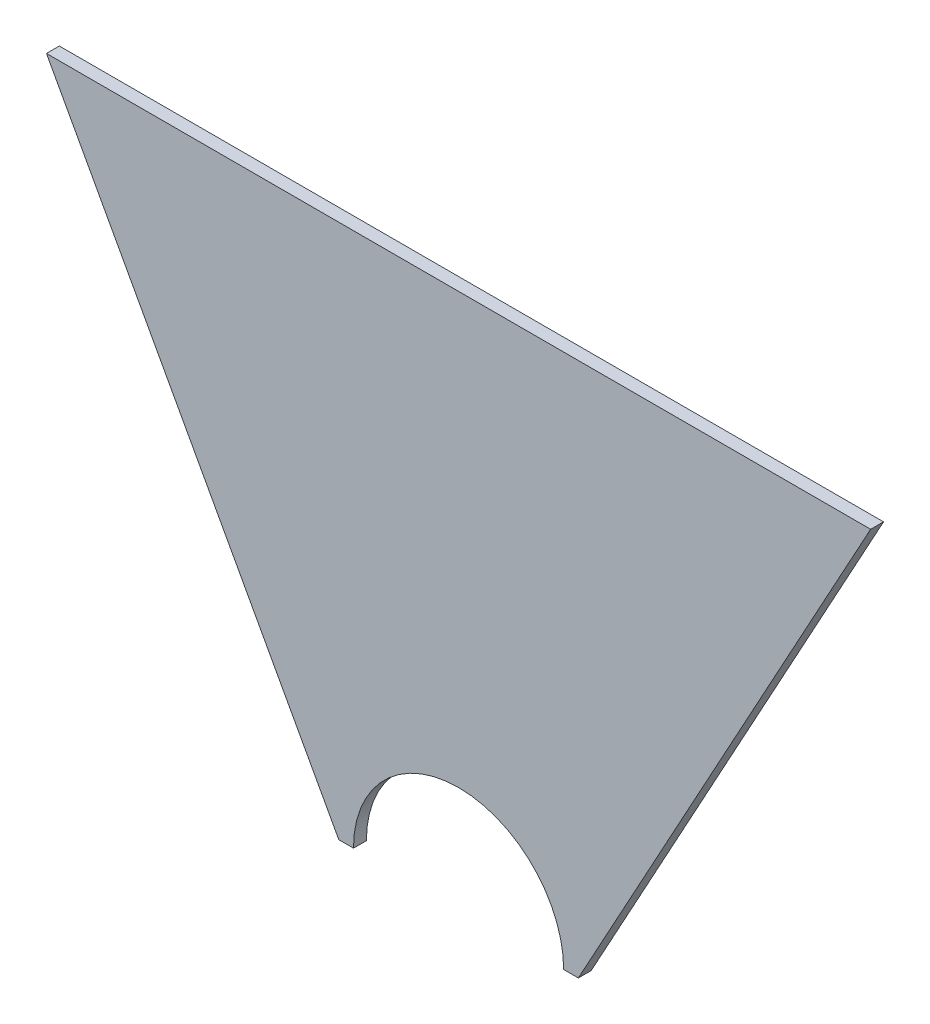
SolidWorks part; units mm, degrees
ref_plane "Front" through (0, 0, 0) normal (0, 0, 1) x (1, 0, 0)
ref_plane "Top" through (0, 0, 0) normal (0, 1, 0) x (1, 0, 0)
ref_plane "Right" through (0, 0, 0) normal (1, 0, 0) x (0, 0, -1)
sketch "Sketch1" plane through (0, 0, 0) normal (0, 0, 1) x (1, 0, 0)
  line L0 (12.954, 0) -> (14.7632, 0)
  line L1 (14.7632, 0) -> (50.8, 65.9219)
  line L2 (50.8, 65.9219) -> (-50.8, 65.9219)
  line L3 (0, 65.9219) -> (0, 0) construction
  line L4 (48.9908, 65.9219) -> (12.954, 0) construction
  line L5 (-14.7632, 0) -> (-50.8, 65.9219)
  line L6 (-12.954, 0) -> (-14.7632, 0)
  arc A0 (12.954, 0) -> (-12.954, 0) centre (0, 0) ccw
  dimension "D1" = 25.908
  dimension "D2" = 1.5875
  dimension "D3" = 50.8
extrude "Boss-Extrude1" add sketch "Sketch1" along normal blind 1.5875
